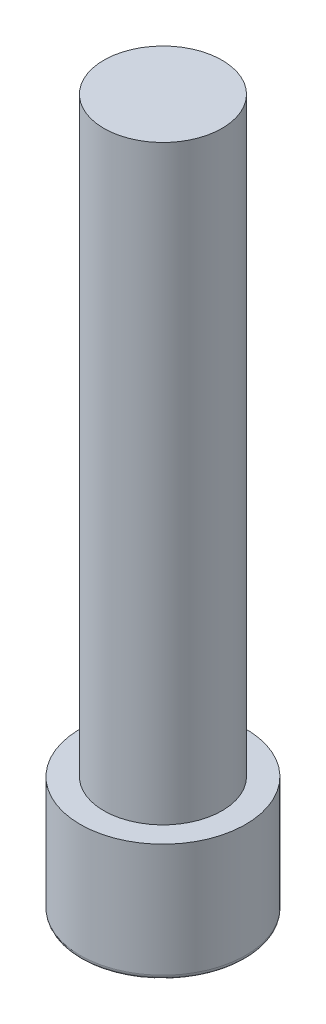
SolidWorks part; units mm, degrees
ref_plane "Front Plane" through (0, 0, 0) normal (0, 0, 1) x (1, 0, 0)
ref_plane "Top Plane" through (0, 0, 0) normal (0, 1, 0) x (1, 0, 0)
ref_plane "Right Plane" through (0, 0, 0) normal (1, 0, 0) x (0, 0, -1)
sketch "Sketch1" plane through (0, 0, 0) normal (0, 1, 0) x (1, 0, 0)
  circle A0 centre (0, 0) radius 3.5
  dimension "D1" = 7
extrude "Boss-Extrude1" add sketch "Sketch1" along normal blind 5
sketch "Sketch2" plane through (0, 5, 0) normal (0, 1, 0) x (1, 0, 0)
  circle A1 centre (0, 0) radius 2.5
extrude "Boss-Extrude2" add sketch "Sketch2" along normal blind 25
sketch "Sketch3" plane through (0, 0, 0) normal (0, -1, 0) x (1, 0, 0)
  line L1 (0, 2) -> (-1.7321, 1)
  line L2 (-1.7321, 1) -> (-1.7321, -1)
  line L3 (-1.7321, -1) -> (0, -2)
  line L4 (0, -2) -> (1.7321, -1)
  line L5 (1.7321, -1) -> (1.7321, 1)
  line L6 (1.7321, 1) -> (0, 2)
  circle A0 centre (0, 0) radius 1.7321 construction
  dimension "D1" = 2
extrude "Cut-Extrude1" cut sketch "Sketch3" against normal blind 2
chamfer "Chamfer1" distance 0.25 angle 45 6 edges at (1.7321, 0, 0) (0.866, 0, -1.5) (-0.866, 0, -1.5) (-1.7321, 0, 0) (-0.866, 0, 1.5) (0.866, 0, 1.5)
fillet "Fillet1" radius 0.2 1 edges at (0, 0, 3.5)
